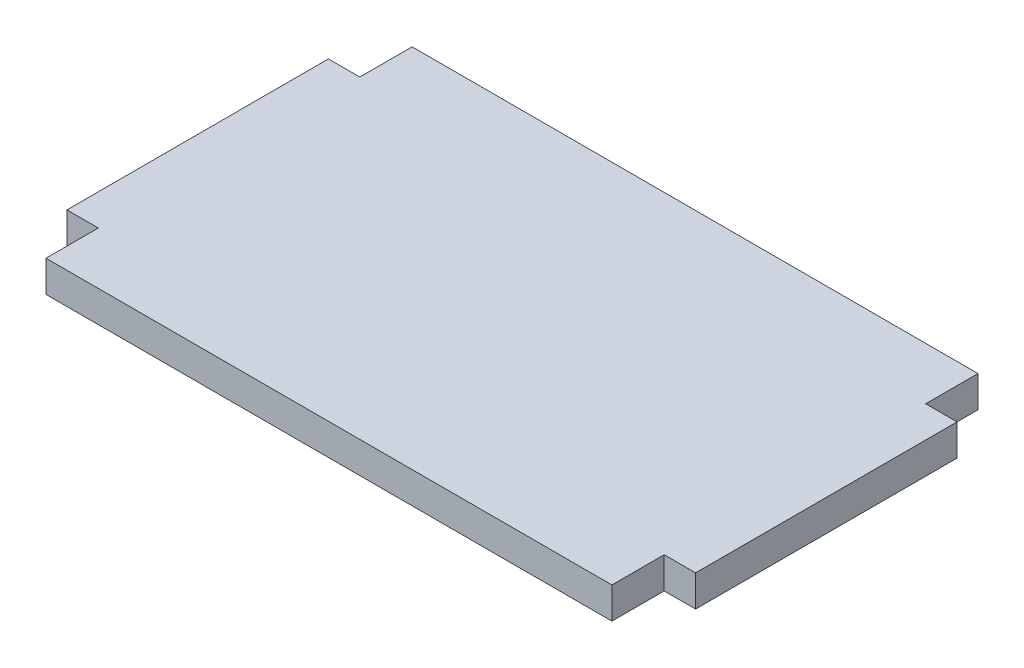
SolidWorks part; units mm, degrees
ref_plane "Front Plane" through (0, 0, 0) normal (0, 0, 1) x (1, 0, 0)
ref_plane "Top Plane" through (0, 0, 0) normal (0, 1, 0) x (1, 0, 0)
ref_plane "Right Plane" through (0, 0, 0) normal (1, 0, 0) x (0, 0, -1)
sketch "Sketch1" plane through (0, 0, 0) normal (0, 1, 0) x (1, 0, 0)
  line L1 (0, 0) -> (108.2, 0)
  line L2 (0, 0) -> (0, 50)
  line L3 (0, 50) -> (108.2, 50)
  line L4 (108.2, 0) -> (108.2, 50)
  line L5 (0, 0) -> (108.2, 50) construction
  line L6 (0, 50) -> (108.2, 0) construction
  point P4 (54.1, 25)
  dimension "D1" = 50
  dimension "D2" = 108.2
extrude "Boss-Extrude1" add sketch "Sketch1" along normal blind 6
sketch "Sketch2" plane through (0, 0, 0) normal (-1, 0, 0) x (0, 0, 1)
  line L1 (-50, 6) -> (0, 6)
  line L2 (-50, 6) -> (-50, 0)
  line L3 (-50, 0) -> (0, 0)
  line L4 (0, 6) -> (0, 0)
  line L5 (-50, 6) -> (0, 0) construction
  line L6 (-50, 0) -> (0, 6) construction
  point P4 (-25, 3)
extrude "Boss-Extrude2" add sketch "Sketch2" along normal blind 6
sketch "Sketch3" plane through (108.2, 0, 0) normal (1, 0, 0) x (0, 0, -1)
  line L1 (0, 6) -> (50, 6)
  line L2 (0, 6) -> (0, 0)
  line L3 (0, 0) -> (50, 0)
  line L4 (50, 6) -> (50, 0)
  line L5 (0, 6) -> (50, 0) construction
  line L6 (0, 0) -> (50, 6) construction
  point P4 (25, 3)
extrude "Boss-Extrude3" add sketch "Sketch3" along normal blind 6
sketch "Sketch4" plane through (0, 0, -50) normal (0, 0, -1) x (-1, 0, 0)
  line L0 (-114.2, 6) -> (6, 6) construction
  line L1 (-108.2, 6) -> (0, 6)
  line L2 (-108.2, 6) -> (-108.2, 0)
  line L3 (-108.2, 0) -> (0, 0)
  line L4 (0, 6) -> (0, 0)
  line L5 (-108.2, 6) -> (0, 0) construction
  line L6 (-108.2, 0) -> (0, 6) construction
  line L7 (-114.2, 0) -> (-114.2, 6) construction
  line L8 (6, 6) -> (6, 0) construction
  point P4 (-54.1, 3)
  dimension "D1" = 6
  dimension "D2" = 6
extrude "Boss-Extrude4" add sketch "Sketch4" along normal blind 10
sketch "Sketch5" plane through (0, 0, 0) normal (0, 0, 1) x (1, 0, 0)
  line L0 (-6, 6) -> (114.2, 6) construction
  line L1 (0, 6) -> (108.2, 6)
  line L2 (0, 6) -> (0, 0)
  line L3 (0, 0) -> (108.2, 0)
  line L4 (108.2, 6) -> (108.2, 0)
  line L5 (0, 6) -> (108.2, 0) construction
  line L6 (0, 0) -> (108.2, 6) construction
  line L7 (-6, 0) -> (114.2, 0) construction
  line L8 (-6, 0) -> (-6, 6) construction
  line L9 (114.2, 6) -> (114.2, 0) construction
  point P4 (54.1, 3)
  dimension "D1" = 6
  dimension "D2" = 6
extrude "Boss-Extrude5" add sketch "Sketch5" along normal blind 10
